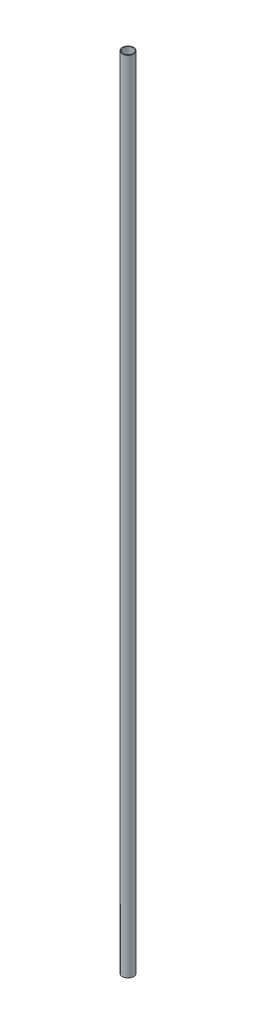
SolidWorks part; units mm, degrees
material "Manual Density from Real Component Longherone"
ref_plane "Piano frontale" through (0, 0, 0) normal (0, 0, 1) x (1, 0, 0)
ref_plane "Piano superiore" through (0, 0, 0) normal (0, 1, 0) x (1, 0, 0)
ref_plane "Piano destro" through (0, 0, 0) normal (1, 0, 0) x (0, 0, -1)
sketch "Schizzo1" plane through (0, 0, 0) normal (0, 1, 0) x (1, 0, 0)
  circle A0 centre (0, 0) radius 7
  circle A1 centre (0, 0) radius 8
  dimension "D1" = 16
  dimension "D2" = 14
extrude "Estrusione-Estrusione1" add sketch "Schizzo1" along normal blind 1120
ref_plane "Piano1" through (0, 5.8, 0) normal (0, 1, 0) x (1, 0, 0)
sketch "Schizzo2" plane through (0, 5.8, 0) normal (0, 1, 0) x (1, 0, 0)
  circle A0 centre (0, 0) radius 8
  dimension "D1" = 16
ref_plane "Piano2" through (0, 17.2, 0) normal (0, 1, 0) x (1, 0, 0)
ref_plane "Piano3" through (0, 34.4, 0) normal (0, 1, 0) x (1, 0, 0)
ref_plane "Piano4" through (0, 57.1, 0) normal (0, 1, 0) x (1, 0, 0)
ref_plane "Piano5" through (0, 85.2, 0) normal (0, 1, 0) x (1, 0, 0)
ref_plane "Piano6" through (0, 118.7, 0) normal (0, 1, 0) x (1, 0, 0)
ref_plane "Piano7" through (0, 157.3, 0) normal (0, 1, 0) x (1, 0, 0)
ref_plane "Piano8" through (0, 200.8, 0) normal (0, 1, 0) x (1, 0, 0)
ref_plane "Piano9" through (0, 249.1, 0) normal (0, 1, 0) x (1, 0, 0)
ref_plane "Piano10" through (0, 301.8, 0) normal (0, 1, 0) x (1, 0, 0)
ref_plane "Piano11" through (0, 358.8, 0) normal (0, 1, 0) x (1, 0, 0)
ref_plane "Piano12" through (0, 419.6, 0) normal (0, 1, 0) x (1, 0, 0)
ref_plane "Piano13" through (0, 484.1, 0) normal (0, 1, 0) x (1, 0, 0)
ref_plane "Piano14" through (0, 551.9, 0) normal (0, 1, 0) x (1, 0, 0)
ref_plane "Piano15" through (0, 622.6, 0) normal (0, 1, 0) x (1, 0, 0)
ref_plane "Piano16" through (0, 695.8, 0) normal (0, 1, 0) x (1, 0, 0)
ref_plane "Piano17" through (0, 771.35, 0) normal (0, 1, 0) x (1, 0, 0)
ref_plane "Piano18" through (0, 848.65, 0) normal (0, 1, 0) x (1, 0, 0)
ref_plane "Piano19" through (0, 927.35, 0) normal (0, 1, 0) x (1, 0, 0)
ref_plane "Piano20" through (0, 1007.05, 0) normal (0, 1, 0) x (1, 0, 0)
ref_plane "Piano21" through (0, 1087.35, 0) normal (0, 1, 0) x (1, 0, 0)
ref_plane "Piano22" through (0, 1127.65, 0) normal (0, 1, 0) x (1, 0, 0)
sketch "Schizzo3" plane through (0, 17.2, 0) normal (0, 1, 0) x (1, 0, 0)
  circle A0 centre (0, 0) radius 8
  dimension "D1" = 16
sketch "Schizzo4" plane through (0, 34.4, 0) normal (0, 1, 0) x (1, 0, 0)
  circle A0 centre (0, 0) radius 8
  dimension "D1" = 16
sketch "Schizzo5" plane through (0, 57.1, 0) normal (0, 1, 0) x (1, 0, 0)
  circle A0 centre (0, 0) radius 8
  dimension "D1" = 16
sketch "Schizzo6" plane through (0, 85.2, 0) normal (0, 1, 0) x (1, 0, 0)
  circle A0 centre (0, 0) radius 8
  dimension "D1" = 16
sketch "Schizzo7" plane through (0, 118.7, 0) normal (0, 1, 0) x (1, 0, 0)
  circle A0 centre (0, 0) radius 8
  dimension "D1" = 16
sketch "Schizzo8" plane through (0, 157.3, 0) normal (0, 1, 0) x (1, 0, 0)
  circle A0 centre (0, 0) radius 8
  dimension "D1" = 16
sketch "Schizzo9" plane through (0, 200.8, 0) normal (0, 1, 0) x (1, 0, 0)
  circle A0 centre (0, 0) radius 8
  dimension "D1" = 16
sketch "Schizzo10" plane through (0, 249.1, 0) normal (0, 1, 0) x (1, 0, 0)
  circle A0 centre (0, 0) radius 8
  dimension "D1" = 16
sketch "Schizzo11" plane through (0, 301.8, 0) normal (0, 1, 0) x (1, 0, 0)
  circle A0 centre (0, 0) radius 8
  dimension "D1" = 16
sketch "Schizzo12" plane through (0, 358.8, 0) normal (0, 1, 0) x (1, 0, 0)
  circle A0 centre (0, 0) radius 8
  dimension "D1" = 16
sketch "Schizzo13" plane through (0, 419.6, 0) normal (0, 1, 0) x (1, 0, 0)
  circle A0 centre (0, 0) radius 8
  dimension "D1" = 16
sketch "Schizzo14" plane through (0, 484.1, 0) normal (0, 1, 0) x (1, 0, 0)
  circle A0 centre (0, 0) radius 8
  dimension "D1" = 16
sketch "Schizzo15" plane through (0, 551.9, 0) normal (0, 1, 0) x (1, 0, 0)
  circle A0 centre (0, 0) radius 8
  dimension "D1" = 16
sketch "Schizzo16" plane through (0, 622.6, 0) normal (0, 1, 0) x (1, 0, 0)
  circle A0 centre (0, 0) radius 8
  dimension "D1" = 16
sketch "Schizzo17" plane through (0, 695.8, 0) normal (0, 1, 0) x (1, 0, 0)
  circle A0 centre (0, 0) radius 8
  dimension "D1" = 16
sketch "Schizzo18" plane through (0, 771.35, 0) normal (0, 1, 0) x (1, 0, 0)
  circle A0 centre (0, 0) radius 8
  dimension "D1" = 16
sketch "Schizzo19" plane through (0, 848.65, 0) normal (0, 1, 0) x (1, 0, 0)
  circle A0 centre (0, 0) radius 8
  dimension "D1" = 16
sketch "Schizzo20" plane through (0, 927.35, 0) normal (0, 1, 0) x (1, 0, 0)
  circle A0 centre (0, 0) radius 8
  dimension "D1" = 16
sketch "Schizzo21" plane through (0, 1007.05, 0) normal (0, 1, 0) x (1, 0, 0)
  circle A0 centre (0, 0) radius 8
  dimension "D1" = 16
sketch "Schizzo22" plane through (0, 1087.35, 0) normal (0, 1, 0) x (1, 0, 0)
  circle A0 centre (0, 0) radius 8
  dimension "D1" = 16
sketch "Schizzo23" plane through (0, 1127.65, 0) normal (0, 1, 0) x (1, 0, 0)
  circle A0 centre (0, 0) radius 8
  dimension "D1" = 16
